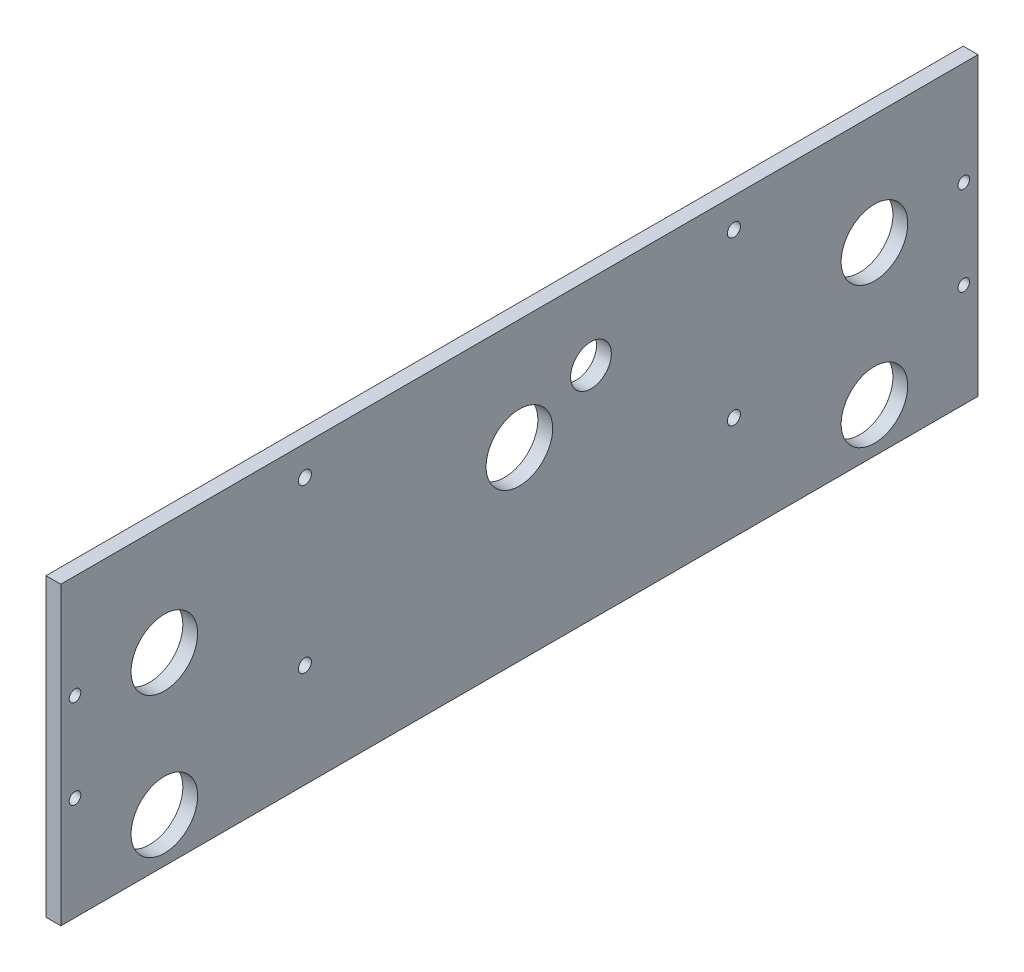
SolidWorks part; units mm, degrees
material "6061-T6 (SS)"
ref_plane "Front Plane" through (0, 0, 0) normal (0, 0, 1) x (1, 0, 0)
ref_plane "Top Plane" through (0, 0, 0) normal (0, 1, 0) x (1, 0, 0)
ref_plane "Right Plane" through (0, 0, 0) normal (1, 0, 0) x (0, 0, -1)
sketch "Sketch1" plane through (0, 0, 0) normal (1, 0, 0) x (0, 0, -1)
  line L1 (-196.85, 63.5) -> (196.85, 63.5)
  line L2 (-196.85, 63.5) -> (-196.85, -63.5)
  line L3 (-196.85, -63.5) -> (196.85, -63.5)
  line L4 (196.85, 63.5) -> (196.85, -63.5)
  line L5 (-196.85, 63.5) -> (196.85, -63.5) construction
  line L6 (-196.85, -63.5) -> (196.85, 63.5) construction
  point P0 (0, 0)
  dimension "D1" = 127
  dimension "D2" = 393.7
extrude "Boss-Extrude1" add sketch "Sketch1" along normal blind 6.35
sketch "Sketch2" plane through (6.35, 0, 0) normal (1, 0, 0) x (0, 0, -1)
  line L0 (-196.85, -63.5) -> (196.85, -63.5) construction
  line L1 (-152.4, 15.875) -> (0, 15.875) construction
  line L2 (-76.2, -34.925) -> (-76.2, 15.875) construction
  line L3 (0, 15.875) -> (152.4, 15.875) construction
  line L4 (76.2, -34.925) -> (76.2, 15.875) construction
  line L5 (196.85, 63.5) -> (-196.85, 63.5) construction
  line L6 (65.278, 53.34) -> (-56.642, 53.34) construction
  line L7 (65.278, 53.34) -> (65.278, -13.97) construction
  line L8 (65.278, -13.97) -> (-56.642, -13.97) construction
  line L9 (-56.642, 53.34) -> (-56.642, -13.97) construction
  line L10 (-196.85, -63.5) -> (196.85, -63.5) construction
  circle A0 centre (0, 15.875) radius 14.2875
  circle A1 centre (-152.4, 15.875) radius 14.2875
  circle A2 centre (152.4, 15.875) radius 14.2875
  circle A3 centre (-152.4, 15.875) radius 38.1 construction
  circle A4 centre (0, 15.875) radius 38.1 construction
  circle A5 centre (152.4, 15.875) radius 38.1 construction
  circle A6 centre (-76.2, -34.925) radius 6.35 construction
  circle A7 centre (76.2, -34.925) radius 6.35 construction
  circle A8 centre (-76.2, 9.525) radius 6.35 construction
  circle A9 centre (76.2, 9.525) radius 6.35 construction
  circle A11 centre (-152.4, -44.45) radius 14.2875
  circle A12 centre (152.4, -44.45) radius 14.2875
  circle A13 centre (0, 15.875) radius 29.21 construction
  circle A14 centre (30.7172, 31.115) radius 5.08 construction
  circle A15 centre (30.7172, 31.115) radius 8.75
  point P11 (0, 0)
  dimension "D1" = 28.575
  dimension "D5" = 76.2
  dimension "D7" = 12.7
  dimension "D14" = 28.575
  dimension "D15" = 19.05
  dimension "D17" = 28.575
  dimension "D20" = 58.42
  dimension "D21" = 10.16
  dimension "D22" = 17.5001
  dimension "D2" = 79.375
  dimension "D3" = 152.4
  dimension "D4" = 152.4
  dimension "D6" = 0
  dimension "D8" = 28.575
  dimension "D9" = 44.45
  dimension "D10" = 56.642
  dimension "D11" = 121.92
  dimension "D12" = 10.16
  dimension "D13" = 49.53
  dimension "D16" = 152.4
  dimension "D18" = 19.05
  dimension "D19" = 152.4
  dimension "D23" = 15.24
extrude "Cut-Extrude1" cut sketch "Sketch2" against normal through all
sketch "Sketch3" plane through (6.35, 0, 0) normal (1, 0, 0) x (0, 0, -1)
  line L0 (-190.754, 19.05) -> (-190.754, -19.05) construction
  line L1 (-196.85, 63.5) -> (-196.85, -63.5) construction
  point P2 (-190.754, 0)
  point P3 (-196.85, 0)
  dimension "D1" = 38.1
  dimension "D2" = 6.096
hole_wizard "#10 Clearance Hole1" positions "Sketch4" profile "Sketch6" hole size "#10" standard "ANSI Inch" end condition through all
sketch "Sketch4" plane through (6.35, 0, 0) normal (1, 0, 0) x (0, 0, -1)
  line L3 (196.85, -63.5) -> (196.85, 63.5) construction
  point P0 (-190.754, 19.05)
  point P3 (-190.754, -19.05)
  point P8 (190.754, 19.05)
  point P10 (190.754, -19.05)
  dimension "D1" = 6.096
  dimension "D2" = 6.096
sketch "Sketch6" plane through (6.35, 19.05, 190.754) normal (0, 1, 0) x (0, 0, -1)
  line L0 (0, 0) -> (0, 6.35)
  line L1 (0, 6.35) -> (2.4892, 6.35)
  line L2 (2.4892, 6.35) -> (2.4892, 0)
  line L5 (2.4892, 0) -> (0, 0)
  line L11 (0, -6.35) -> (0, 107.95) construction
  dimension "Thru Hole Dia." = 4.9784
  dimension "Thru Hole Depth" = 6.35
sketch "Sketch24" plane through (0, 0, 0) normal (-1, 0, 0) x (0, 0, 1)
  line L0 (-196.85, -63.5) -> (-196.85, 63.5) construction
  line L1 (-196.85, 63.5) -> (196.85, 63.5) construction
  point P0 (-92.075, -19.05)
  point P1 (-92.075, 50.8)
  point P2 (92.075, -19.05)
  point P4 (92.075, 50.8)
  point P10 (0, 0)
  point P11 (0, 0)
  point P12 (0, 0)
  point P13 (0, 0)
  dimension "D1" = 12.7
  dimension "D2" = 104.775
  dimension "D3" = 184.15
  dimension "D4" = 12.7
  dimension "D5" = 69.85
  dimension "D6" = 69.85
hole_wizard "CSK for #10 Flat Head Machine Screw2" positions "Sketch25" profile "Sketch26" countersink size "#10" standard "ANSI Inch" end condition through all
sketch "Sketch25" plane through (0, 0, 0) normal (-1, 0, 0) x (0, 0, 1)
  point P0 (-92.075, 50.8)
  point P3 (-92.075, -19.05)
  point P6 (92.075, -19.05)
  point P9 (92.075, 50.8)
sketch "Sketch26" plane through (0, 50.8, -92.075) normal (0, 1, 0) x (0, 0, 1)
  line L0 (0, 0) -> (0, 6.35)
  line L1 (0, 6.35) -> (2.8067, 6.35)
  line L2 (2.8067, 6.35) -> (2.8067, 2.396)
  line L3 (2.8067, 2.396) -> (4.8895, 0)
  line L5 (4.8895, 0) -> (0, 0)
  line L6 (-2.8067, 2.396) -> (-4.8895, 0) construction
  line L11 (0, -6.35) -> (0, 107.95) construction
  dimension "Thru Hole Dia." = 5.6134
  dimension "Thru Hole Depth" = 6.35
  dimension "Near C'Sink Dia." = 9.779
  dimension "Near C'Sink Angle" = 82
